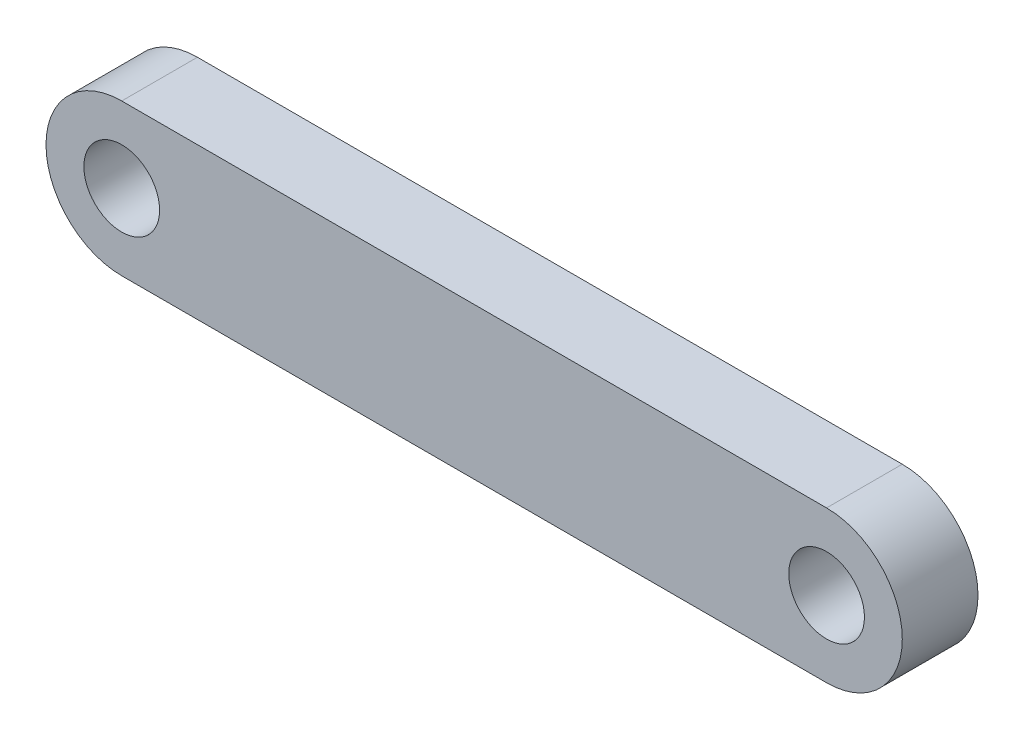
SolidWorks part; units mm, degrees
ref_plane "Front Plane" through (0, 0, 0) normal (0, 0, 1) x (1, 0, 0)
ref_plane "Top Plane" through (0, 0, 0) normal (0, 1, 0) x (1, 0, 0)
ref_plane "Right Plane" through (0, 0, 0) normal (1, 0, 0) x (0, 0, -1)
sketch "Sketch1" plane through (0, 0, 0) normal (0, 0, 1) x (1, 0, 0)
  line L0 (0, 0) -> (18.62, 0) construction
  line L1 (0, 2) -> (18.62, 2)
  line L2 (0, -2) -> (18.62, -2)
  arc A0 (0, 2) -> (0, -2) centre (0, 0) ccw
  arc A1 (18.62, -2) -> (18.62, 2) centre (18.62, 0) ccw
  circle A2 centre (0, 0) radius 1
  circle A3 centre (18.62, 0) radius 1
  point P3 (9.31, 0)
  dimension "D1" = 2
  dimension "D3" = 2
  dimension "D4" = 2
  dimension "D2" = 18.62
extrude "Boss-Extrude1" add sketch "Sketch1" along normal blind 2
